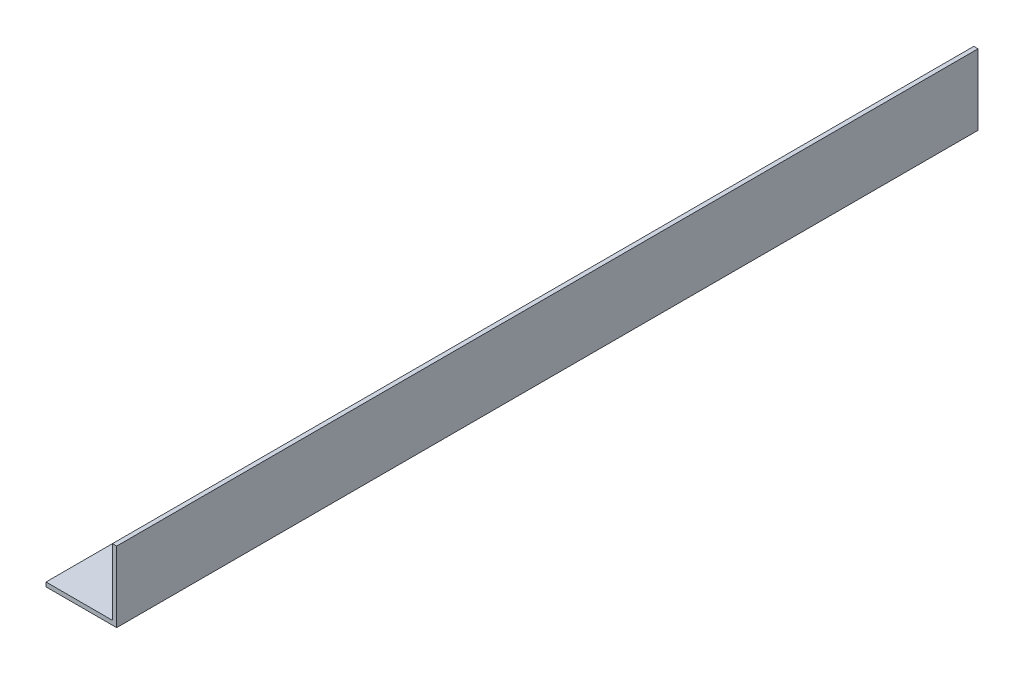
SolidWorks part; units mm, degrees
ref_plane "Front Plane" through (0, 0, 0) normal (0, 0, 1) x (1, 0, 0)
ref_plane "Top Plane" through (0, 0, 0) normal (0, 1, 0) x (1, 0, 0)
ref_plane "Right Plane" through (0, 0, 0) normal (1, 0, 0) x (0, 0, -1)
sketch "Sketch1" plane through (0, 0, 0) normal (0, 0, 1) x (1, 0, 0)
  line L0 (-50, 0) -> (0, 0)
  line L1 (0, 0) -> (0, 50)
  line L2 (0, 50) -> (-3, 50)
  line L3 (-3, 50) -> (-3, 3)
  line L4 (-3, 3) -> (-50, 3)
  line L5 (-50, 0) -> (-50, 3)
  line L6 (-1.5, 50) -> (0, 50) construction
  line L7 (-50, 1.5) -> (-50, 0) construction
  dimension "Vert" = 50
  dimension "Horz" = 50
  dimension "Thickness" = 3
sketch "Sketch2" plane through (0, 0, 0) normal (1, 0, 0) x (0, 0, -1)
  line L0 (-304.8, 0) -> (304.8, 0) construction
  point P0 (-292.608, 0)
  point P4 (0, 0)
  point P5 (292.608, 0)
  dimension "Length" = 609.6
  dimension "D1" = 12.192
  dimension "D2" = 12.192
sketch "Sketch3" plane through (0, 0, 0) normal (0, 0, 1) x (1, 0, 0)
  line L0 (-50, 0) -> (0, 0) construction
  line L1 (0, 0) -> (0, 50) construction
  line L2 (0, 50) -> (-3, 50) construction
  line L3 (-3, 50) -> (-3, 3) construction
  line L4 (-3, 3) -> (-50, 3) construction
  line L5 (-50, 0) -> (-50, 3) construction
  line L6 (-50, 0) -> (0, 0)
  line L7 (0, 0) -> (0, 50)
  line L8 (0, 50) -> (-3, 50)
  line L9 (-3, 50) -> (-3, 3)
  line L10 (-3, 3) -> (-50, 3)
  line L11 (-50, 0) -> (-50, 3)
extrude "Boss-Extrude1" add sketch "Sketch3" along normal up to vertex (304.8 mm away) and the other way up to vertex (304.8 mm away) up to point (0, 0, 304.8) other way up to point (0, 0, -304.8)
equation "\"D1@Sketch2\"=\"Length@Sketch2\"*.02"
equation "\"D2@Sketch2\"=\"D1@Sketch2\""
